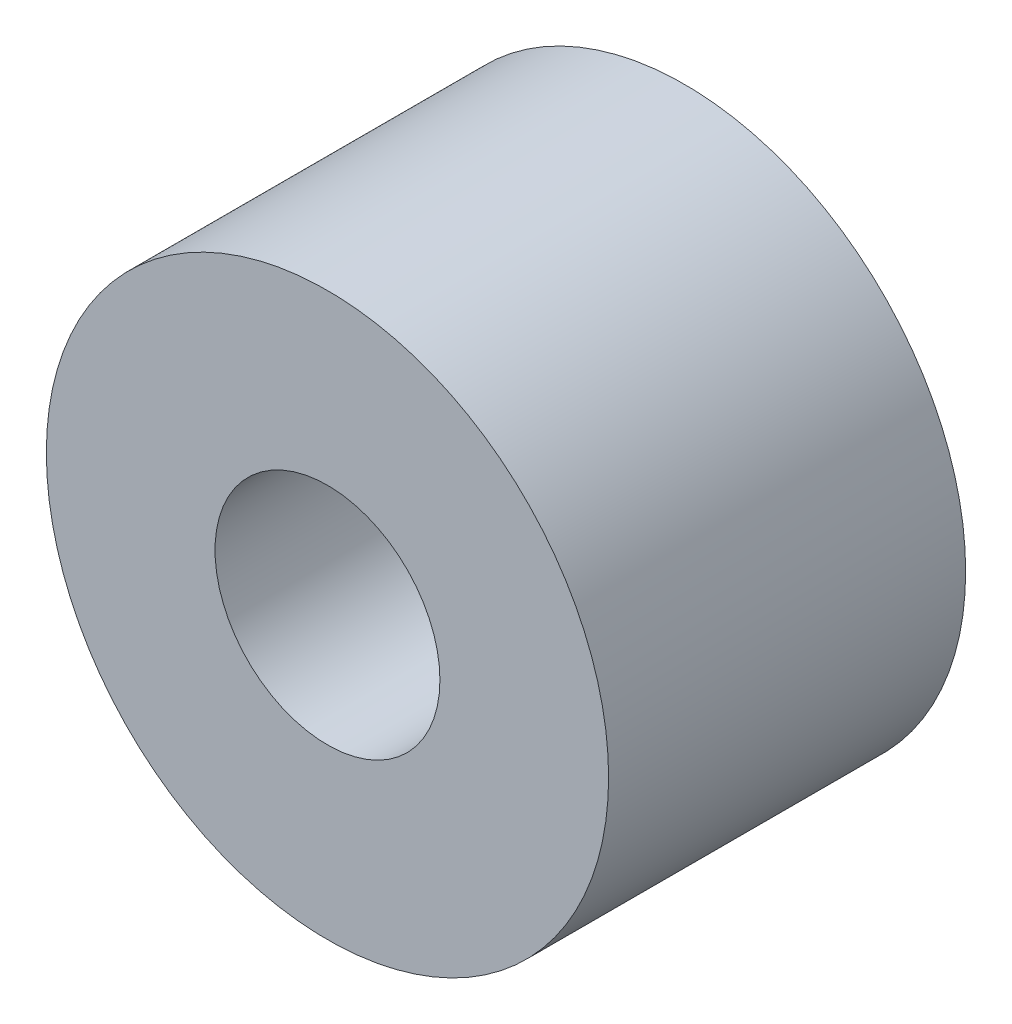
SolidWorks part; units mm, degrees
material "ABS"
ref_plane "Front Plane" through (0, 0, 0) normal (0, 0, 1) x (1, 0, 0)
ref_plane "Top Plane" through (0, 0, 0) normal (0, 1, 0) x (1, 0, 0)
ref_plane "Right Plane" through (0, 0, 0) normal (1, 0, 0) x (0, 0, -1)
sketch "Sketch1" plane through (0, 0, 0) normal (0, 0, 1) x (1, 0, 0)
  circle A0 centre (0, 0) radius 5
  circle A1 centre (0, 0) radius 2
  dimension "D1" = 10
  dimension "D2" = 4
extrude "Boss-Extrude1" add sketch "Sketch1" along normal blind 6.35
